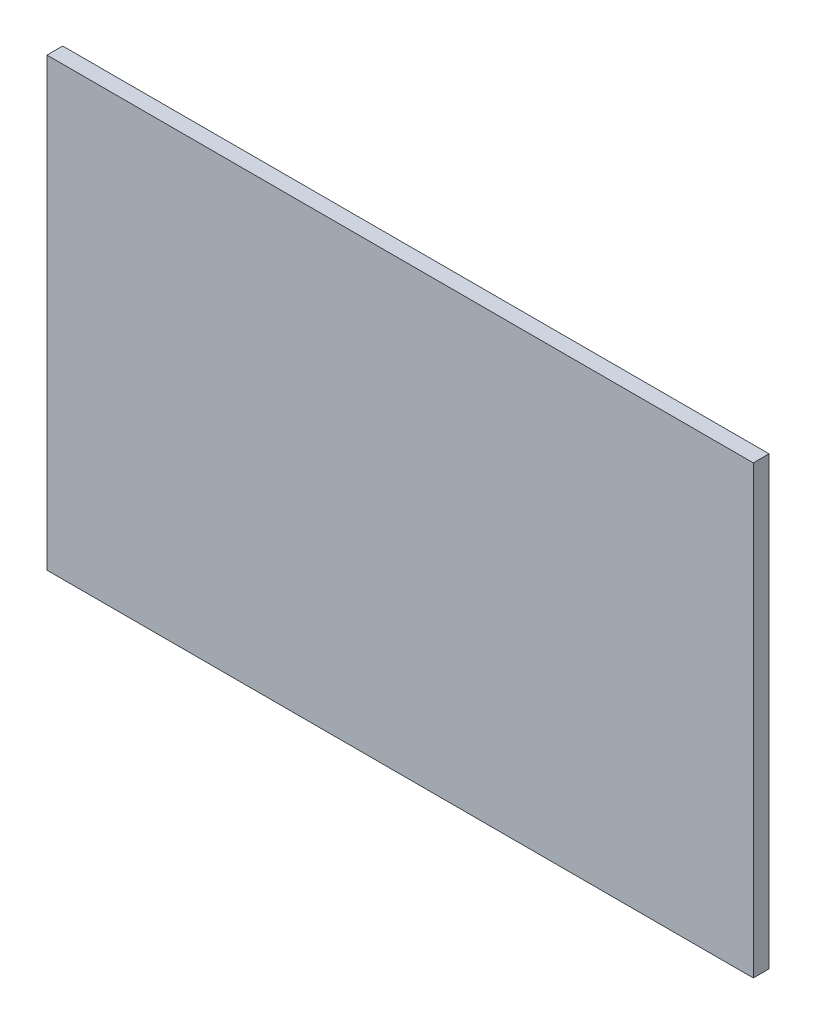
SolidWorks part; units mm, degrees
material "A-Glass Fiber"
ref_plane "Front Plane" through (0, 0, 0) normal (0, 0, 1) x (1, 0, 0)
ref_plane "Top Plane" through (0, 0, 0) normal (0, 1, 0) x (1, 0, 0)
ref_plane "Right Plane" through (0, 0, 0) normal (1, 0, 0) x (0, 0, -1)
sketch "Sketch1" plane through (0, 0, 0) normal (0, 0, 1) x (1, 0, 0)
  line L1 (0, 0) -> (784.225, 0)
  line L2 (0, 0) -> (0, 495.3)
  line L3 (0, 495.3) -> (784.225, 495.3)
  line L4 (784.225, 0) -> (784.225, 495.3)
  dimension "D1" = 495.3
  dimension "D2" = 784.225
extrude "Boss-Extrude1" add sketch "Sketch1" along normal blind 17.4625
